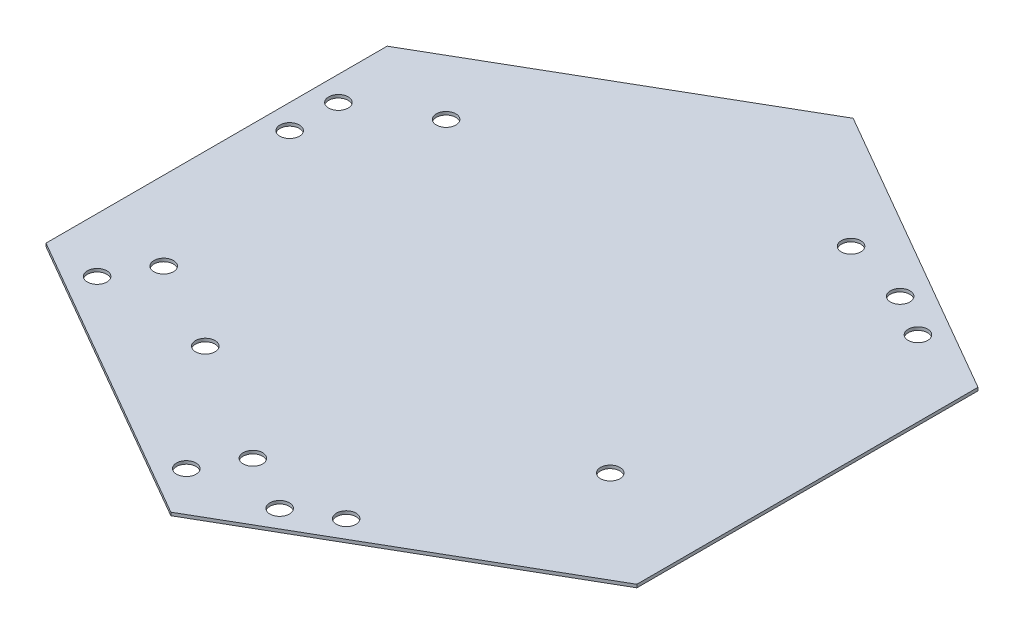
SolidWorks part; units mm, degrees
material "5052-H32"
ref_plane "Front Plane" through (0, 0, 0) normal (0, 0, 1) x (1, 0, 0)
ref_plane "Top Plane" through (0, 0, 0) normal (0, 1, 0) x (1, 0, 0)
ref_plane "Right Plane" through (0, 0, 0) normal (1, 0, 0) x (0, 0, -1)
sketch "Sketch1" plane through (0, 0, 0) normal (0, 1, 0) x (1, 0, 0)
  line L0 (13.3228, -73.8757) -> (24.3213, -67.5257) construction
  line L1 (0, 88.9) -> (-76.9897, 44.45)
  line L2 (-76.9897, 44.45) -> (-76.9897, -44.45)
  line L3 (-76.9897, -44.45) -> (0, -88.9)
  line L4 (0, -88.9) -> (76.9897, -44.45)
  line L5 (76.9897, -44.45) -> (76.9897, 44.45)
  line L6 (76.9897, 44.45) -> (0, 88.9)
  line L7 (24.3213, -67.5257) -> (27.4963, -73.025) construction
  line L8 (-70.6397, 12.7) -> (-76.9897, 12.7) construction
  line L9 (-70.6397, 25.4) -> (-70.6397, 12.7) construction
  line L10 (46.3184, 54.8257) -> (49.4934, 60.325) construction
  line L11 (57.3169, 48.4757) -> (46.3184, 54.8257) construction
  circle A0 centre (0, 0) radius 76.9897 construction
  circle A1 centre (13.3228, -73.8757) radius 2.54
  circle A2 centre (24.3213, -67.5257) radius 2.54
  circle A7 centre (-70.6397, 12.7) radius 2.54
  circle A8 centre (-70.6397, 25.4) radius 2.54
  circle A9 centre (46.3184, 54.8257) radius 2.54
  circle A10 centre (57.3169, 48.4757) radius 2.54
  point P13 (38.4948, -66.675)
  point P28 (3.175, -1.8331)
  point P29 (0, 0)
  dimension "D2" = 5.08
  dimension "D3" = 6.35
  dimension "D4" = 12.7
  dimension "D1" = 177.8
  dimension "D5" = 12.7
  dimension "D6" = 3
extrude "Boss-Extrude1" add sketch "Sketch1" along normal blind 0.8128
sketch "Sketch2" plane through (0, 0.8128, 0) normal (0, 1, 0) x (1, 0, 0)
  line L1 (17.6188, -76.1634) -> (79.2138, 30.5223) construction
  line L2 (17.6188, -76.1634) -> (-83.5676, -17.7434) construction
  line L3 (-83.5676, -17.7434) -> (-21.9726, 88.9423) construction
  line L4 (79.2138, 30.5223) -> (-21.9726, 88.9423) construction
  line L7 (-76.9897, -44.45) -> (0, -88.9) construction
  circle A0 centre (28.6206, 59.7323) radius 2.54
  circle A1 centre (48.4163, -22.8205) radius 2.54
  circle A2 centre (-52.7701, 35.5995) radius 2.54
  circle A3 centre (-32.9744, -46.9534) radius 2.54
  dimension "D5" = 5.08
  dimension "D1" = 123.19
  dimension "D2" = 116.84
  dimension "D3" = 57.15
  dimension "D4" = 53.34
extrude "Cut-Extrude1" cut sketch "Sketch2" against normal through all
sketch "Sketch3" plane through (0, 0.8128, 0) normal (0, 1, 0) x (1, 0, 0)
  line L0 (-62.8161, -45.3007) -> (-65.9911, -50.8) construction
  line L2 (-76.9897, -44.45) -> (0, -88.9) construction
  line L3 (-62.8161, -45.3007) -> (-7.8235, -77.0507) construction
  line L4 (-35.3198, -61.1757) -> (-38.4948, -66.675) construction
  line L5 (-56.4661, -34.3022) -> (-62.8161, -45.3007) construction
  line L6 (-56.4661, -34.3022) -> (-1.4735, -66.0522) construction
  circle A1 centre (-7.8235, -77.0507) radius 2.54
  circle A2 centre (-62.8161, -45.3007) radius 2.54
  circle A3 centre (-56.4661, -34.3022) radius 2.54
  circle A4 centre (-1.4735, -66.0522) radius 2.54
  dimension "D1" = 5.08
  dimension "D2" = 6.35
  dimension "D3" = 63.5
  dimension "D4" = 12.7
extrude "Cut-Extrude2" cut sketch "Sketch3" against normal through all
